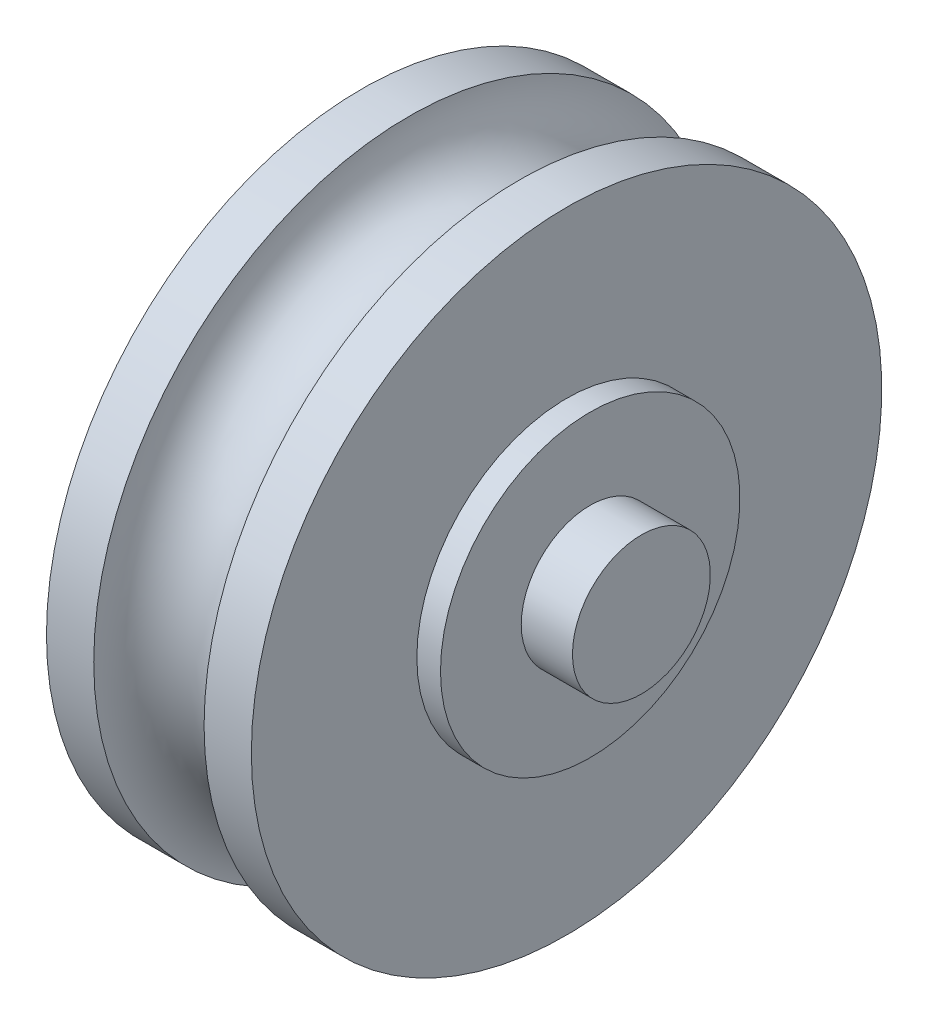
SolidWorks part; units mm, degrees
ref_plane "Front Plane" through (0, 0, 0) normal (0, 0, 1) x (1, 0, 0)
ref_plane "Top Plane" through (0, 0, 0) normal (0, 1, 0) x (1, 0, 0)
ref_plane "Right Plane" through (0, 0, 0) normal (1, 0, 0) x (0, 0, -1)
sketch "Sketch1" plane through (0, 0, 0) normal (0, 0, 1) x (1, 0, 0)
  line L0 (0, 0) -> (0, 69.984) construction
  line L1 (0, 0) -> (52.2681, 0) construction
  line L2 (2.6, 3.8) -> (2.6, 8)
  line L3 (2.6, 3.8) -> (3.2, 3.8)
  line L4 (3.2, 3.8) -> (3.2, 1.75)
  line L5 (3.2, 1.75) -> (4.5, 1.75)
  line L6 (4.5, 1.75) -> (4.5, 0)
  line L7 (2.6, 8) -> (1.4, 8)
  line L8 (-2.6, 8) -> (-1.4, 8)
  line L9 (-4.5, 1.75) -> (-4.5, 0)
  line L10 (-3.2, 1.75) -> (-4.5, 1.75)
  line L11 (-3.2, 3.8) -> (-3.2, 1.75)
  line L12 (-2.6, 3.8) -> (-3.2, 3.8)
  line L13 (-2.6, 3.8) -> (-2.6, 8)
  line L14 (-4.5, 0) -> (4.5, 0)
  arc A0 (1.4, 8) -> (-1.4, 8) centre (0, 8) cw
  dimension "D1" = 2.6
  dimension "D2" = 3.8
  dimension "D3" = 8
  dimension "D4" = 3.2
  dimension "D5" = 4.5
  dimension "D6" = 1.75
  dimension "D7" = 1.2
revolve "Revolve1" add sketch "Sketch1" angle 360 about L1
